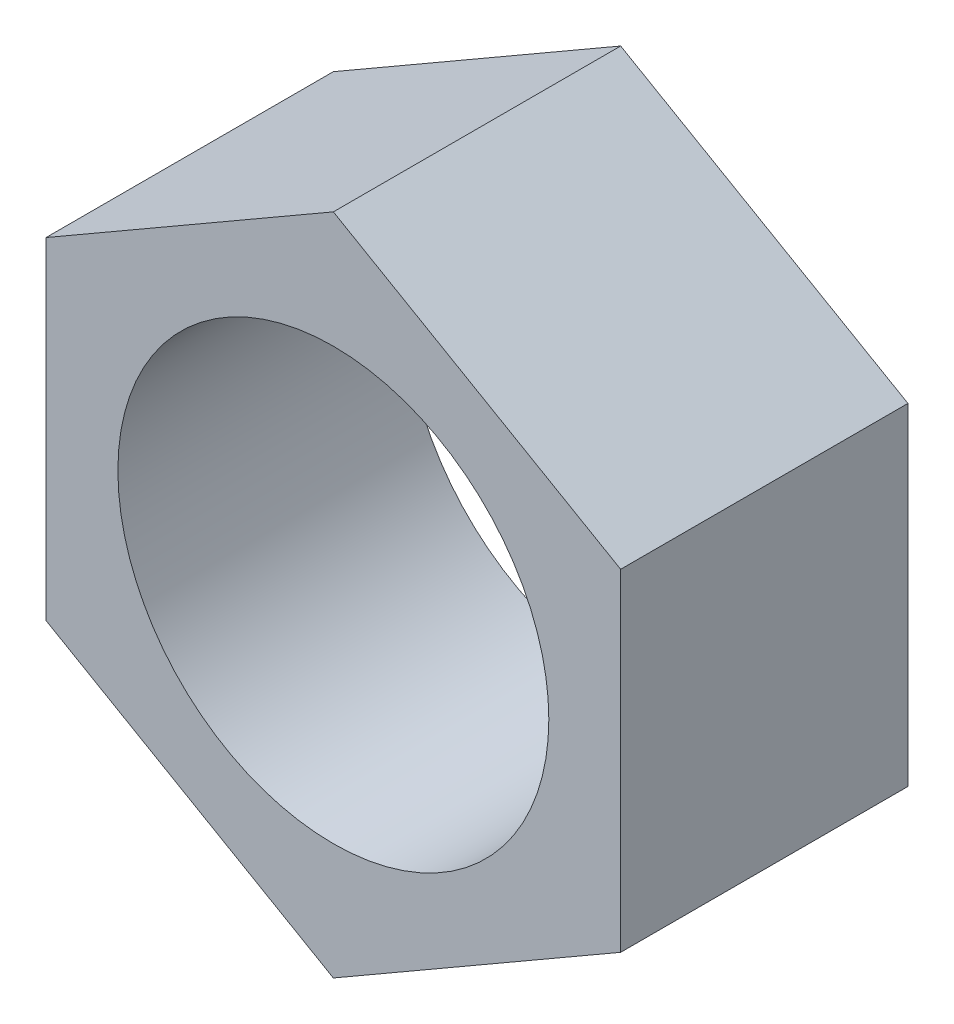
SolidWorks part; units mm, degrees
ref_plane "Front Plane" through (0, 0, 0) normal (0, 0, 1) x (1, 0, 0)
ref_plane "Top Plane" through (0, 0, 0) normal (0, 1, 0) x (1, 0, 0)
ref_plane "Right Plane" through (0, 0, 0) normal (1, 0, 0) x (0, 0, -1)
sketch "Sketch1" plane through (0, 0, 0) normal (0, 0, 1) x (1, 0, 0)
  line L1 (0, 11.547) -> (-10, 5.7735)
  line L2 (-10, 5.7735) -> (-10, -5.7735)
  line L3 (-10, -5.7735) -> (0, -11.547)
  line L4 (0, -11.547) -> (10, -5.7735)
  line L5 (10, -5.7735) -> (10, 5.7735)
  line L6 (10, 5.7735) -> (0, 11.547)
  circle A0 centre (0, 0) radius 10 construction
  circle A1 centre (0, 0) radius 7.5
  dimension "D1" = 20
  dimension "D2" = 15
extrude "Boss-Extrude1" add sketch "Sketch1" along normal blind 10 contours L5 L6 L1 L2 L3 L4 A1
